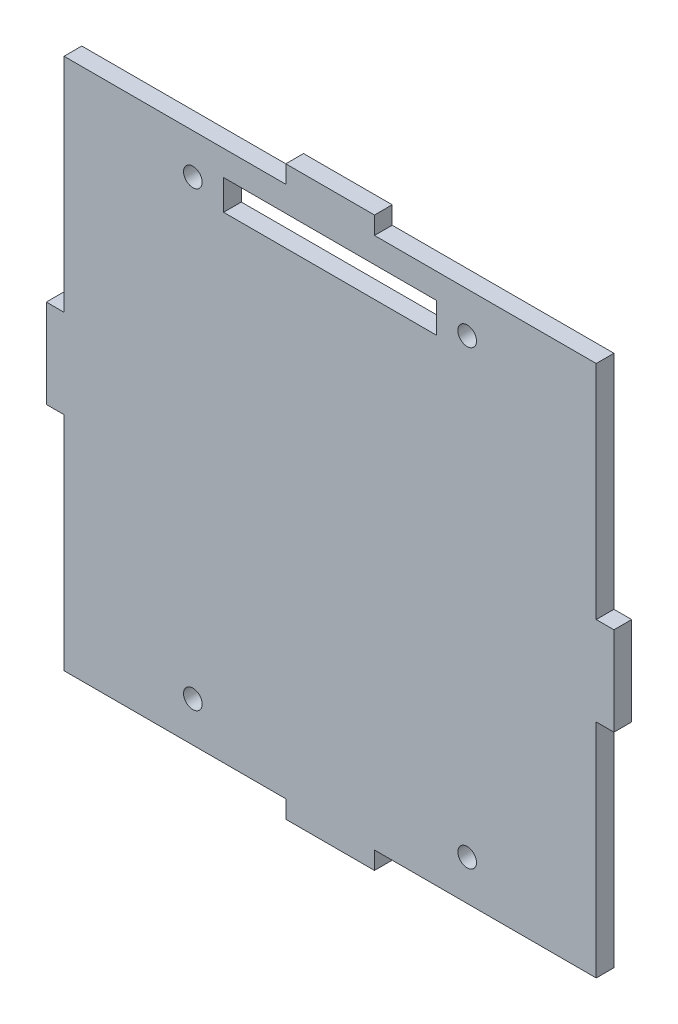
SolidWorks part; units mm, degrees
ref_plane "前视基准面" through (0, 0, 0) normal (0, 0, 1) x (1, 0, 0)
ref_plane "上视基准面" through (0, 0, 0) normal (0, 1, 0) x (1, 0, 0)
ref_plane "右视基准面" through (0, 0, 0) normal (1, 0, 0) x (0, 0, -1)
sketch "草图1" plane through (0, 0, 0) normal (0, 0, 1) x (1, 0, 0)
  line L0 (-4.5977, -13.4325) -> (-4.5977, -38.4325)
  line L1 (-64.5977, 21.5675) -> (-39.5977, 21.5675)
  line L3 (-64.5977, -38.4325) -> (-39.5977, -38.4325)
  line L4 (-4.5977, 21.5675) -> (-4.5977, -3.4325)
  line L7 (-34.5977, -40.4325) -> (-29.5977, -40.4325)
  line L8 (-34.5977, -40.4325) -> (-39.5977, -40.4325)
  line L9 (-39.5977, -40.4325) -> (-39.5977, -38.4325)
  line L10 (-29.5977, -40.4325) -> (-29.5977, -38.4325)
  line L11 (-39.5977, 21.5675) -> (-39.5977, 23.5675)
  line L12 (-39.5977, 23.5675) -> (-29.5977, 23.5675)
  line L13 (-29.5977, 23.5675) -> (-29.5977, 21.5675)
  line L16 (-4.5977, -13.4325) -> (-2.5977, -13.4325)
  line L17 (-2.5977, -13.4325) -> (-2.5977, -3.4325)
  line L18 (-2.5977, -3.4325) -> (-4.5977, -3.4325)
  line L22 (-29.5977, 21.5675) -> (-4.5977, 21.5675)
  line L23 (-29.5977, -38.4325) -> (-4.5977, -38.4325)
  line L25 (-64.5977, 21.5675) -> (-64.5977, -3.4325)
  line L27 (-66.5977, -8.4325) -> (-66.5977, -3.4325)
  line L28 (-66.5977, -8.4325) -> (-66.5977, -13.4325)
  line L29 (-66.5977, -13.4325) -> (-64.5977, -13.4325)
  line L31 (-64.5977, -3.4325) -> (-66.5977, -3.4325)
  line L32 (-64.5977, -13.4325) -> (-64.5977, -38.4325)
  dimension "D1" = 60
  dimension "D2" = 60
extrude "凸台-拉伸1" add sketch "草图1" along normal blind 2
sketch "草图2" plane through (0, 0, 0) normal (0, 0, 1) x (1, 0, 0)
  line L9 (-50.9929, -34.4217) -> (-50.0091, -32.8624) construction
  line L10 (-50.9929, 17.5577) -> (-50.0091, 15.9984) construction
  line L12 (-50.0758, 19.0813) -> (-50.0758, 15.9963) construction
  line L13 (-18.0963, -33.9103) -> (-71.4534, -33.9103) construction
  line L14 (-19.1463, 19.0393) -> (-19.1463, 15.9467) construction
  line L15 (-17.2258, 17.0463) -> (-51.9258, 17.0463) construction
  line L16 (-50.0758, -32.8603) -> (-50.0758, -34.9603) construction
  line L19 (-19.1833, -32.8609) -> (-18.2151, -34.3955) construction
  line L21 (-34.5961, -8.4325) -> (-18.2227, 17.5196) construction
  line L22 (-19.1463, -32.8603) -> (-19.1463, -44.168) construction
  circle A0 centre (-50.0758, 17.0463) radius 1.05
  circle A1 centre (-19.1463, 17.0043) radius 1.0576
  circle A2 centre (-19.1463, -33.9103) radius 1.05
  circle A3 centre (-50.0758, -33.9103) radius 1.05
  point P11 (-34.5957, -8.432)
  point P19 (-51.0227, 19.0675)
  point P22 (-17.2477, -8.4325)
extrude "切除-拉伸1" cut sketch "草图2" along normal blind 6
sketch "草图4" plane through (0, 0, 0) normal (0, 0, 1) x (1, 0, 0)
  line L7 (-32.8787, 18.7206) -> (-22.6111, 18.7206)
  line L8 (-32.8787, 18.7206) -> (-46.6111, 18.7206)
  line L9 (-32.8787, 15.3253) -> (-22.6111, 15.3253)
  line L10 (-32.8787, 15.3253) -> (-46.6111, 15.3253)
  line L11 (-46.6111, 15.3253) -> (-46.6111, 18.7206)
  line L12 (-22.6111, 15.3253) -> (-22.6111, 18.7206)
  point P7 (-38.0758, 17.03)
  point P8 (-20.8787, 17.0066)
  point P9 (-38.0758, 18.73)
extrude "切除-拉伸2" cut sketch "草图4" along normal blind 4
